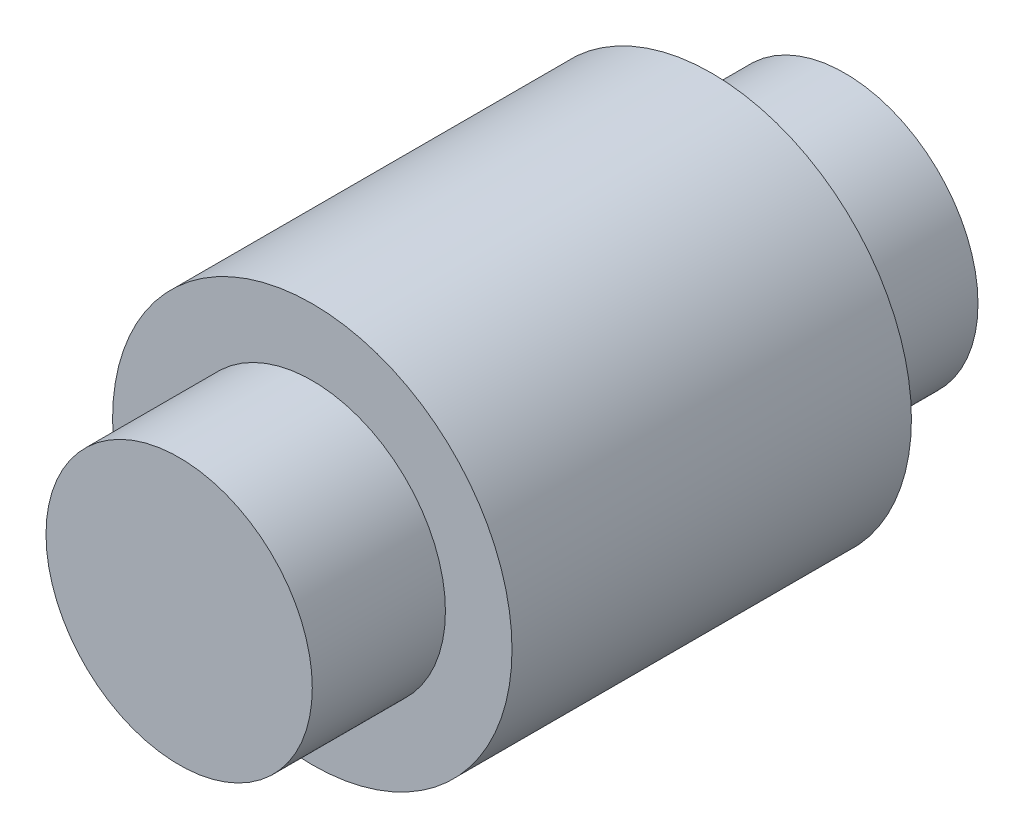
SolidWorks part; units mm, degrees
ref_plane "정면" through (0, 0, 0) normal (0, 0, 1) x (1, 0, 0)
ref_plane "윗면" through (0, 0, 0) normal (0, 1, 0) x (1, 0, 0)
ref_plane "우측면" through (0, 0, 0) normal (1, 0, 0) x (0, 0, -1)
sketch "스케치1" plane through (0, 0, 0) normal (0, 0, 1) x (1, 0, 0)
  circle A0 centre (0, 0) radius 5
  dimension "D1" = 10
extrude "보스-돌출1" add sketch "스케치1" along normal blind 5
sketch "스케치2" plane through (0, 0, 5) normal (0, 0, 1) x (1, 0, 0)
  circle A0 centre (0, 0) radius 7.5
  dimension "D1" = 15
extrude "보스-돌출2" add sketch "스케치2" along normal blind 15
ref_plane "평면1" through (0, 0, 12.5) normal (0, 0, -1) x (-1, 0, 0)
mirror "대칭 복사1" about plane through (0, 0, 12.5) normal (0, 0, -1) of "보스-돌출1"
